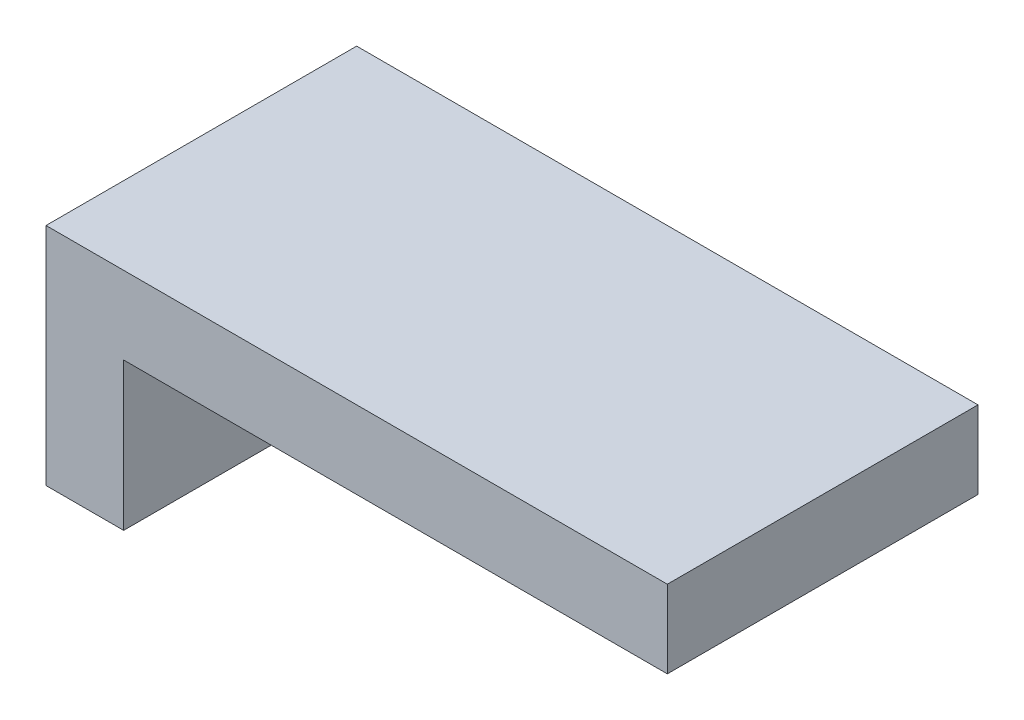
SolidWorks part; units mm, degrees
material "PP Kopolimer"
ref_plane "Front Plane" through (0, 0, 0) normal (0, 0, 1) x (1, 0, 0)
ref_plane "Top Plane" through (0, 0, 0) normal (0, 1, 0) x (1, 0, 0)
ref_plane "Right Plane" through (0, 0, 0) normal (1, 0, 0) x (0, 0, -1)
sketch "Szkic1" plane through (0, 0, 0) normal (0, 1, 0) x (1, 0, 0)
  line L1 (0, 0) -> (-1, 0)
  line L2 (0, 0) -> (0, 4)
  line L3 (0, 4) -> (-1, 4)
  line L4 (-1, 0) -> (-1, 4)
  dimension "D1" = 1
  dimension "D2" = 4
extrude "Dodanie-wyciągnięcie1" add sketch "Szkic1" along normal blind 1.9 contours L4 L3 L2 L1
sketch "Szkic2" plane through (0, 1.9, 0) normal (0, 1, 0) x (1, 0, 0)
  line L1 (-1, 4) -> (0, 4)
  line L2 (-1, 4) -> (-1, 0)
  line L3 (-1, 0) -> (0, 0)
  line L4 (0, 4) -> (0, 0)
extrude "Dodanie-wyciągnięcie2" add sketch "Szkic2" along normal blind 1
sketch "Szkic3" plane through (0, 0, 0) normal (1, 0, 0) x (0, 0, -1)
  line L0 (0, 2.9) -> (0, 0) construction
  line L1 (4, 2.9) -> (0, 2.9)
  line L2 (4, 2.9) -> (4, 1.9)
  line L3 (4, 1.9) -> (0, 1.9)
  line L4 (0, 2.9) -> (0, 1.9)
extrude "Dodanie-wyciągnięcie3" add sketch "Szkic3" along normal blind 7
